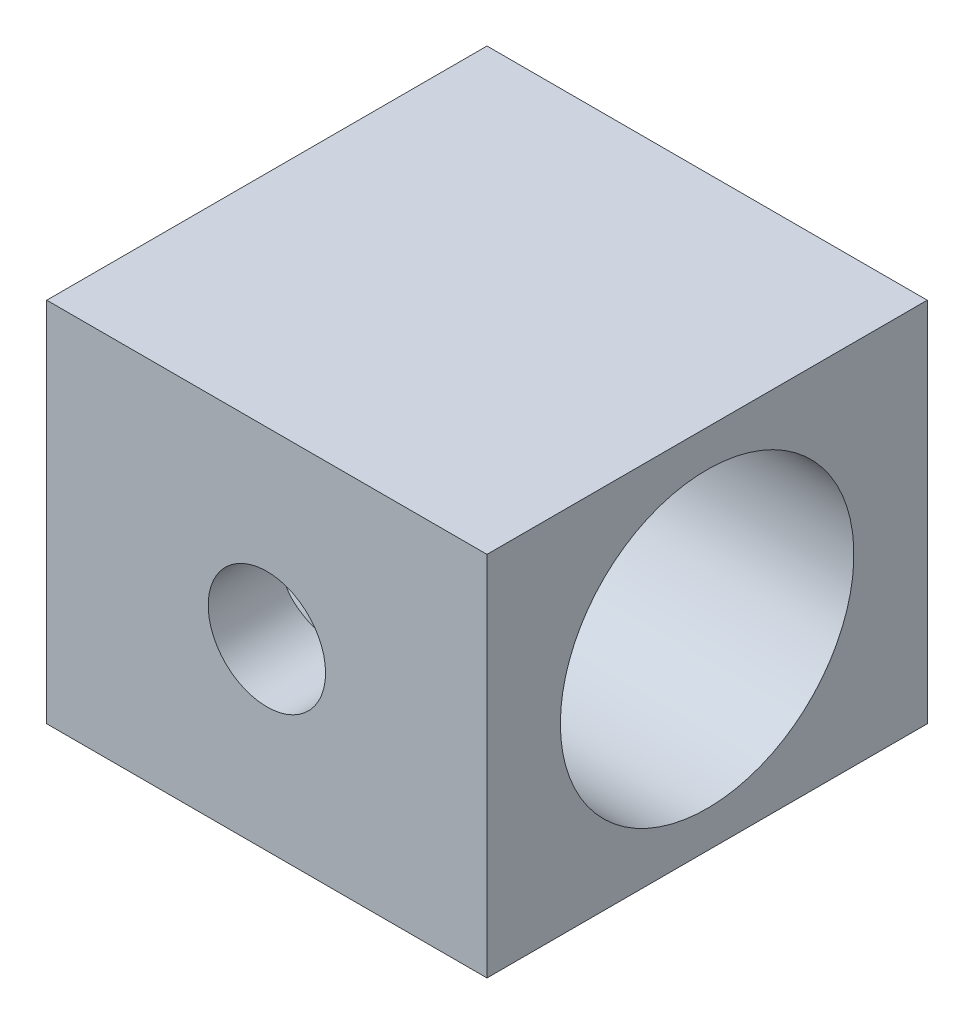
SolidWorks part; units mm, degrees
ref_plane "前视基准面" through (0, 0, 0) normal (0, 0, 1) x (1, 0, 0)
ref_plane "上视基准面" through (0, 0, 0) normal (0, 1, 0) x (1, 0, 0)
ref_plane "右视基准面" through (0, 0, 0) normal (1, 0, 0) x (0, 0, -1)
other "Configuration Table"
sketch "草图1" plane through (0, 0, 0) normal (0, 0, 1) x (1, 0, 0)
  line L1 (-15, -12.5) -> (15, -12.5)
  line L2 (-15, -12.5) -> (-15, 12.5)
  line L3 (-15, 12.5) -> (15, 12.5)
  line L4 (15, -12.5) -> (15, 12.5)
  line L5 (-15, -12.5) -> (15, 12.5) construction
  line L6 (-15, 12.5) -> (15, -12.5) construction
  point P0 (0, 0)
  dimension "D1" = 30
  dimension "D2" = 25
extrude "凸台-拉伸1" add sketch "草图1" along normal mid plane 30
sketch "草图3" plane through (-15, 0, 0) normal (-1, 0, 0) x (0, 0, 1)
  circle A0 centre (0, 0) radius 10
  dimension "D1" = 20
extrude "切除-拉伸1" cut sketch "草图3" against normal through all
sketch "草图4" plane through (0, 0, 15) normal (0, 0, 1) x (1, 0, 0)
  circle A0 centre (0, 0) radius 4
  dimension "D1" = 8
extrude "切除-拉伸2" cut sketch "草图4" against normal up to surface (15 mm away) up to plane "前视基准面"
